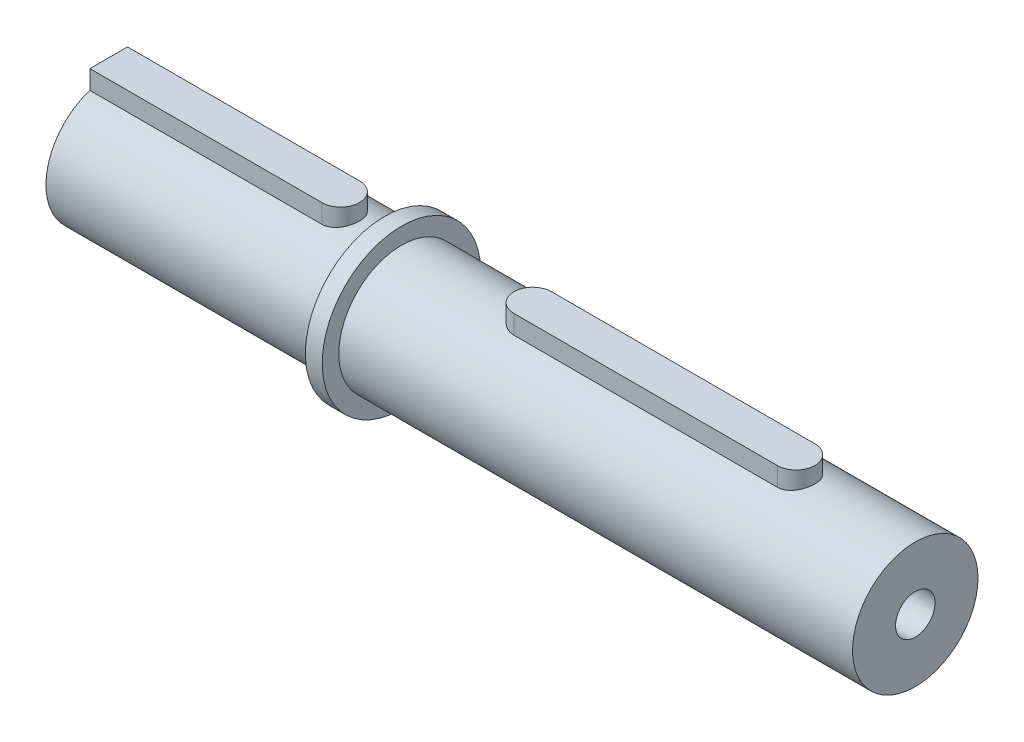
SolidWorks part; units mm, degrees
ref_plane "Front Plane" through (0, 0, 0) normal (0, 0, 1) x (1, 0, 0)
ref_plane "Top Plane" through (0, 0, 0) normal (0, 1, 0) x (1, 0, 0)
ref_plane "Right Plane" through (0, 0, 0) normal (1, 0, 0) x (0, 0, -1)
sketch "Sketch1" plane through (0, 0, 0) normal (1, 0, 0) x (0, 0, -1)
  circle A0 centre (0, 0) radius 10.033
  dimension "D1" = 20.066
extrude "Boss-Extrude1" add sketch "Sketch1" against normal blind 2.1336
sketch "Sketch2" plane through (0, 0, 0) normal (1, 0, 0) x (0, 0, -1)
  circle A0 centre (0, 0) radius 7.9375
  dimension "D1" = 15.875
extrude "Boss-Extrude2" add sketch "Sketch2" along normal blind 65.024
hole_wizard "M6 Tapped Hole1" positions "Sketch4" profile "Sketch3" tap size "M6" standard "DIN"
sketch "Sketch4" plane through (65.024, 0, 0) normal (1, 0, 0) x (0, 0, -1)
  point P0 (0, 0)
sketch "Sketch3" plane through (65.024, 0, 0) normal (0, 1, 0) x (0, 0, -1)
  line L0 (0, 0) -> (0, 16.4882)
  line L1 (0, 16.4882) -> (2.5, 14.986)
  line L2 (2.5, 14.986) -> (2.5, 0)
  line L5 (2.5, 0) -> (0, 0)
  line L10 (0, 16.4882) -> (-2.5, 14.986) construction
  line L11 (0, -6.35) -> (0, 107.95) construction
  dimension "Tap Drill Dia." = 5
  dimension "Tap Drill Depth" = 14.986
  dimension "Drill Angle" = 118
cosmetic thread "Hole Thread1" parameters "D1"=9.906, "D2"=6
sketch "Sketch5" plane through (-2.1336, 0, 0) normal (-1, 0, 0) x (0, 0, 1)
  circle A0 centre (0, 0) radius 7.9375
  dimension "D1" = 15.875
extrude "Boss-Extrude3" add sketch "Sketch5" along normal blind 34.925
ref_plane "Plane1" through (0, 5.1943, 0) normal (0, 1, 0) x (1, 0, 0)
sketch "Sketch7" plane through (0, 5.1943, 0) normal (0, 1, 0) x (1, 0, 0)
  line L0 (16.6052, 0) -> (49.9427, 0) construction
  line L1 (16.6052, 2.3813) -> (49.9427, 2.3813)
  line L2 (16.6052, -2.3813) -> (49.9427, -2.3813)
  line L3 (65.024, -7.9375) -> (65.024, 7.9375) construction
  line L4 (-37.0586, 0) -> (-7.6898, 0) construction
  line L5 (-37.0586, 7.9375) -> (-37.0586, -7.9375) construction
  line L6 (-37.0586, 2.3812) -> (-7.6898, 2.3812)
  line L7 (-37.0586, -2.3812) -> (-7.6898, -2.3812)
  line L8 (-37.0586, 2.3812) -> (-37.0586, -2.3812)
  arc A0 (16.6052, 2.3813) -> (16.6052, -2.3813) centre (16.6052, 0) ccw
  arc A1 (49.9427, -2.3813) -> (49.9427, 2.3813) centre (49.9427, 0) ccw
  arc A3 (-7.6898, -2.3812) -> (-7.6898, 2.3812) centre (-7.6898, 0) ccw
  point P3 (33.274, 0)
  point P14 (-22.3742, 0)
  dimension "D1" = 33.3375
  dimension "D2" = 15.0812
  dimension "D3" = 4.7625
  dimension "D4" = 4.7625
  dimension "D5" = 29.3687
extrude "Boss-Extrude4" add sketch "Sketch7" along normal blind 4.7625
